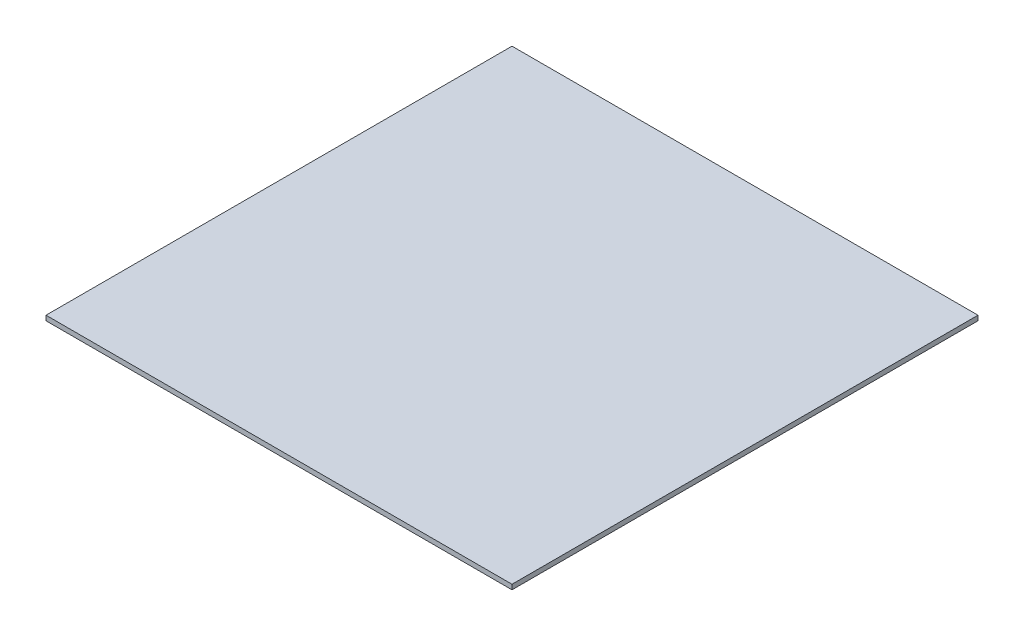
SolidWorks part; units mm, degrees
ref_plane "Front Plane" through (0, 0, 0) normal (0, 0, 1) x (1, 0, 0)
ref_plane "Top Plane" through (0, 0, 0) normal (0, 1, 0) x (1, 0, 0)
ref_plane "Right Plane" through (0, 0, 0) normal (1, 0, 0) x (0, 0, -1)
sketch "Sketch1" plane through (0, 0, 0) normal (0, 1, 0) x (1, 0, 0)
  line L0 (38.1, 304.8) -> (38.1, 0)
  line L1 (0, 0) -> (304.8, 0)
  line L2 (0, 0) -> (0, 304.8)
  line L3 (0, 304.8) -> (304.8, 304.8)
  line L4 (304.8, 0) -> (304.8, 304.8)
  line L5 (76.2, 304.8) -> (76.2, 0)
  line L6 (152.4, 304.8) -> (152.4, 0)
  line L7 (114.3, 304.8) -> (114.3, 0)
  line L8 (190.5, 304.8) -> (190.5, 0)
  line L9 (228.6, 304.8) -> (228.6, 0)
  line L10 (266.7, 304.8) -> (266.7, 0)
  line L11 (0, 266.7) -> (304.8, 266.7)
  line L12 (0, 228.6) -> (304.8, 228.6)
  line L13 (0, 152.4) -> (304.8, 152.4)
  line L14 (0, 190.5) -> (304.8, 190.5)
  line L15 (0, 114.3) -> (304.8, 114.3)
  line L16 (0, 76.2) -> (304.8, 76.2)
  line L17 (0, 38.1) -> (304.8, 38.1)
  dimension "D1" = 304.8
  dimension "D2" = 38.1
  dimension "D3" = 38.1
  dimension "D4" = 38.1
  dimension "D5" = 38.1
  dimension "D6" = 38.1
  dimension "D7" = 38.1
  dimension "D8" = 38.1
  dimension "D9" = 38.1
  dimension "D10" = 38.1
  dimension "D11" = 38.1
  dimension "D12" = 38.1
  dimension "D13" = 38.1
sketch "Sketch2" plane through (0, 0, 0) normal (1, 0, 0) x (0, 0, -1)
  line L1 (0, 0) -> (304.8, 0)
  line L2 (0, 0) -> (0, -3.175)
  line L3 (0, -3.175) -> (304.8, -3.175)
  line L4 (304.8, 0) -> (304.8, -3.175)
extrude "Boss-Extrude1" add sketch "Sketch2" along normal blind 304.8
